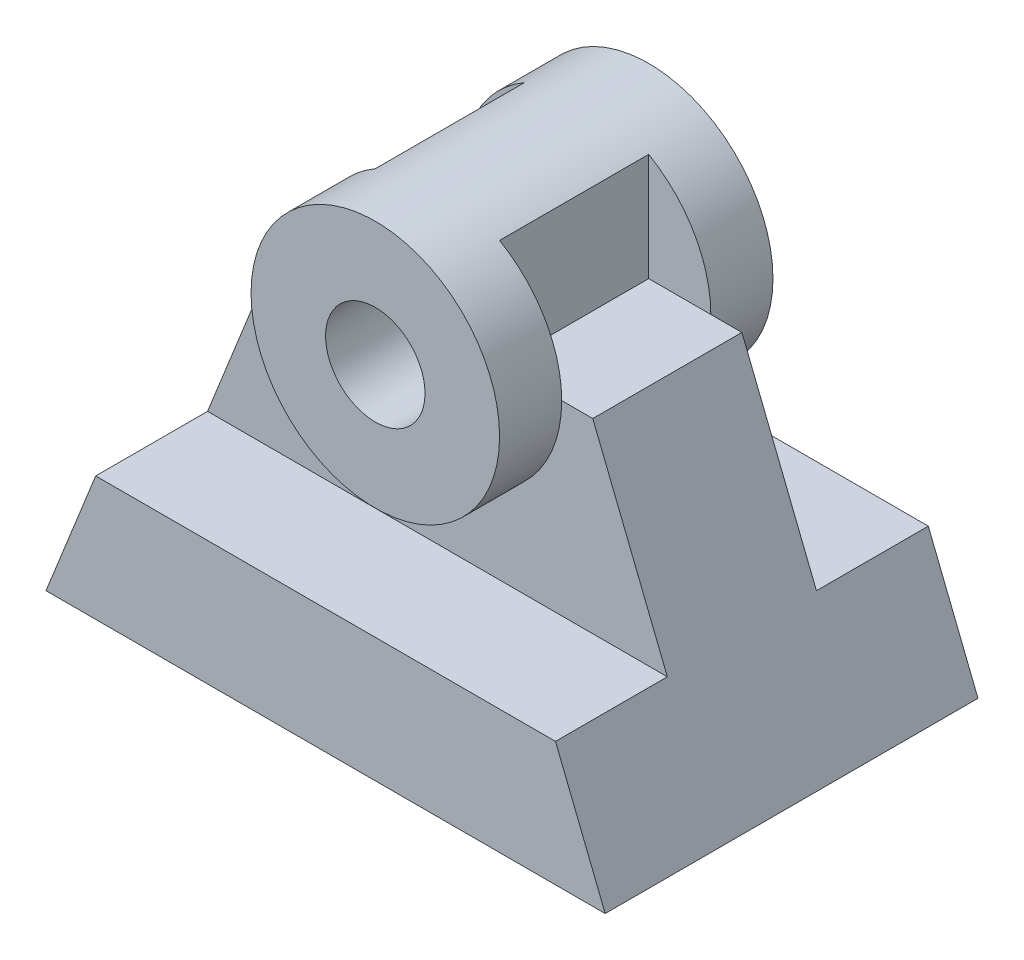
SolidWorks part; units mm, degrees
ref_plane "Front Plane" through (0, 0, 0) normal (0, 0, 1) x (1, 0, 0)
ref_plane "Top Plane" through (0, 0, 0) normal (0, 1, 0) x (1, 0, 0)
ref_plane "Right Plane" through (0, 0, 0) normal (1, 0, 0) x (0, 0, -1)
sketch "Sketch1" plane through (0, 0, 0) normal (0, 0, 1) x (1, 0, 0)
  line L0 (-45, 0) -> (45, 0)
  line L1 (45, 0) -> (25, 50)
  line L2 (25, 50) -> (-25, 50)
  line L3 (-25, 50) -> (-45, 0)
  line L4 (0, 0) -> (0, 50) construction
  dimension "D1" = 90
  dimension "D2" = 50
  dimension "D3" = 50
extrude "Boss-Extrude1" add sketch "Sketch1" along normal mid plane 60
sketch "Sketch3" plane through (0, 0, 0) normal (1, 0, 0) x (0, 0, -1)
  line L0 (-30, 0) -> (30, 0) construction
  line L1 (30, 50) -> (12, 50)
  line L2 (30, 50) -> (30, 20)
  line L3 (30, 20) -> (12, 20)
  line L4 (12, 50) -> (12, 20)
  line L5 (0, 0) -> (0, 61.7508) construction
  line L6 (-12, 50) -> (-12, 20)
  line L7 (-30, 20) -> (-12, 20)
  line L8 (-30, 50) -> (-30, 20)
  line L9 (-30, 50) -> (-12, 50)
  dimension "D1" = 18
  dimension "D2" = 20
extrude "Cut-Extrude1" cut sketch "Sketch3" against normal through all both and the other way through all
sketch "Sketch4" plane through (0, 0, 0) normal (0, 0, 1) x (1, 0, 0)
  line L0 (-25, 50) -> (25, 50) construction
  circle A0 centre (0, 50) radius 20
  circle A1 centre (0, 50) radius 8
  dimension "D1" = 16
  dimension "D2" = 40
extrude "Boss-Extrude2" add sketch "Sketch4" along normal mid plane 44
sketch "Sketch5" plane through (0, 0, 0) normal (0, 0, 1) x (1, 0, 0)
  line L0 (-20, 50) -> (-10, 50)
  line L1 (-10, 50) -> (-10, 67.3205)
  line L2 (0, 0) -> (0, 77.8228) construction
  line L3 (10, 50) -> (10, 67.3205)
  line L4 (20, 50) -> (10, 50)
  line L5 (-25, 50) -> (-20, 50) construction
  circle A0 centre (0, 50) radius 20 construction
  arc A1 (-10, 67.3205) -> (-20, 50) centre (0, 50) ccw
  arc A2 (20, 50) -> (10, 67.3205) centre (0, 50) ccw
  dimension "D1" = 20
extrude "Cut-Extrude2" cut sketch "Sketch5" against normal mid plane 24
sketch "Sketch6" plane through (0, 0, 12) normal (0, 0, 1) x (1, 0, 0)
  circle A0 centre (0, 50) radius 8 construction
  circle A1 centre (0, 50) radius 8
extrude "Cut-Extrude3" cut sketch "Sketch6" against normal through all both and the other way through all
